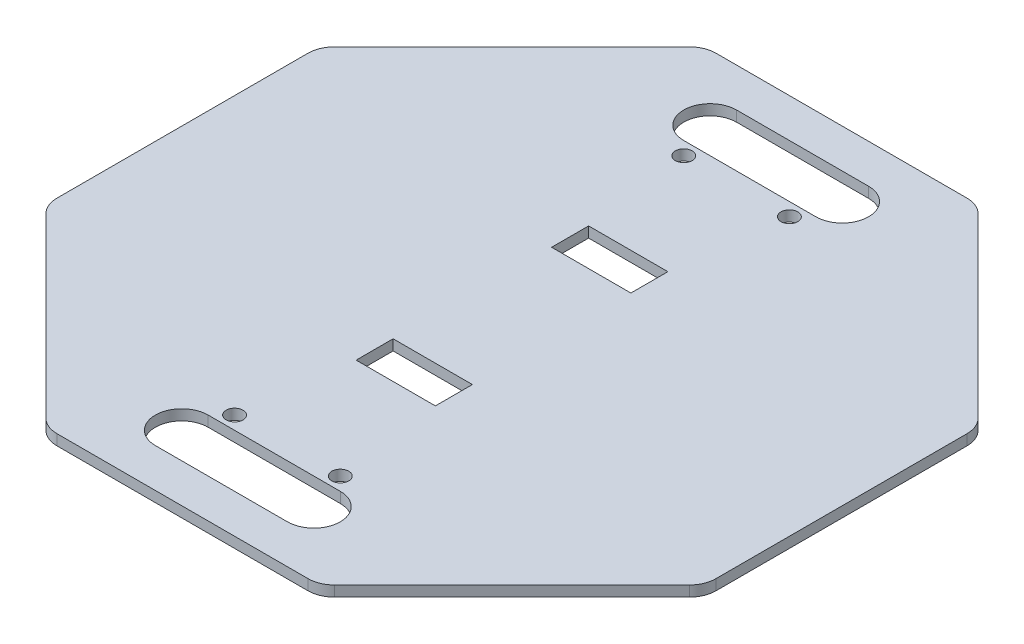
SolidWorks part; units mm, degrees
ref_plane "Front Plane" through (0, 0, 0) normal (0, 0, 1) x (1, 0, 0)
ref_plane "Top Plane" through (0, 0, 0) normal (0, 1, 0) x (1, 0, 0)
ref_plane "Right Plane" through (0, 0, 0) normal (1, 0, 0) x (0, 0, -1)
sketch "Sketch1" plane through (0, 0, 0) normal (0, 1, 0) x (1, 0, 0)
  line L0 (0, 67.5) -> (0, -67.5) construction
  line L1 (-67.5, 0) -> (67.5, 0) construction
  line L2 (62.3619, 25.8311) -> (62.3619, -25.8311)
  line L3 (-25.8311, 62.3619) -> (25.8311, 62.3619)
  line L4 (0, 0) -> (62.3619, 25.8311) construction
  line L5 (-25.8311, 62.3619) -> (0, 0) construction
  line L6 (-25.8311, -62.3619) -> (25.8311, -62.3619)
  line L7 (-62.3619, 25.8311) -> (-62.3619, -25.8311)
  line L8 (12.5, -50) -> (-12.5, -50) construction
  line L9 (12.5, -55) -> (-12.5, -55)
  line L10 (12.5, -45) -> (-12.5, -45)
  line L11 (12.5, 50) -> (-12.5, 50) construction
  line L12 (12.5, 55) -> (-12.5, 55)
  line L13 (12.5, 45) -> (-12.5, 45)
  line L14 (14.3249, -42.5) -> (-21.367, -42.5) construction
  line L15 (-7.5, -22) -> (7.5, -22)
  line L16 (-7.5, -22) -> (-7.5, -15)
  line L17 (-7.5, -15) -> (7.5, -15)
  line L18 (7.5, -22) -> (7.5, -15)
  line L19 (-7.5, -22) -> (7.5, -15) construction
  line L20 (-7.5, -15) -> (7.5, -22) construction
  line L21 (-7.5, 22) -> (-7.5, 15)
  line L22 (-7.5, 22) -> (7.5, 22)
  line L23 (7.5, 22) -> (7.5, 15)
  line L24 (-7.5, 15) -> (7.5, 15)
  line L25 (25.8311, -62.3619) -> (62.3619, -25.8311)
  line L26 (62.3619, 25.8311) -> (25.8311, 62.3619)
  line L27 (-25.8311, 62.3619) -> (-62.3619, 25.8311)
  line L28 (-62.3619, -25.8311) -> (-25.8311, -62.3619)
  circle A0 centre (0, 0) radius 67.5
  arc A1 (12.5, -55) -> (12.5, -45) centre (12.5, -50) ccw
  arc A2 (-12.5, -45) -> (-12.5, -55) centre (-12.5, -50) ccw
  arc A3 (12.5, 55) -> (12.5, 45) centre (12.5, 50) cw
  arc A4 (-12.5, 45) -> (-12.5, 55) centre (-12.5, 50) cw
  circle A5 centre (10, -42.5) radius 1.6
  circle A6 centre (-10, -42.5) radius 1.6
  circle A7 centre (-10, 42.5) radius 1.6
  circle A8 centre (10, 42.5) radius 1.6
  point P17 (0, -50)
  point P24 (0, 50)
  point P29 (0, -18.5)
  dimension "D1" = 135
  dimension "D10" = 3.2
  dimension "D11" = 10
  dimension "D12" = 2.5
  dimension "D2" = 22.5
  dimension "D3" = 22.5
  dimension "D4" = 10
  dimension "D5" = 25
  dimension "D6" = 50
  dimension "D7" = 7
  dimension "D8" = 23
  dimension "D9" = 15
extrude "Boss-Extrude1" add sketch "Sketch1" along normal blind 2 contours L6 A0 L2 L3 L7
fillet "Fillet1" radius 5 8 edges at (-25.8311, 1, 62.3619) (-62.3619, 1, 25.8311) (-62.3619, 1, -25.8311) (-25.8311, 1, -62.3619) (25.8311, 1, -62.3619) (62.3619, 1, -25.8311) (62.3619, 1, 25.8311) (25.8311, 1, 62.3619)
